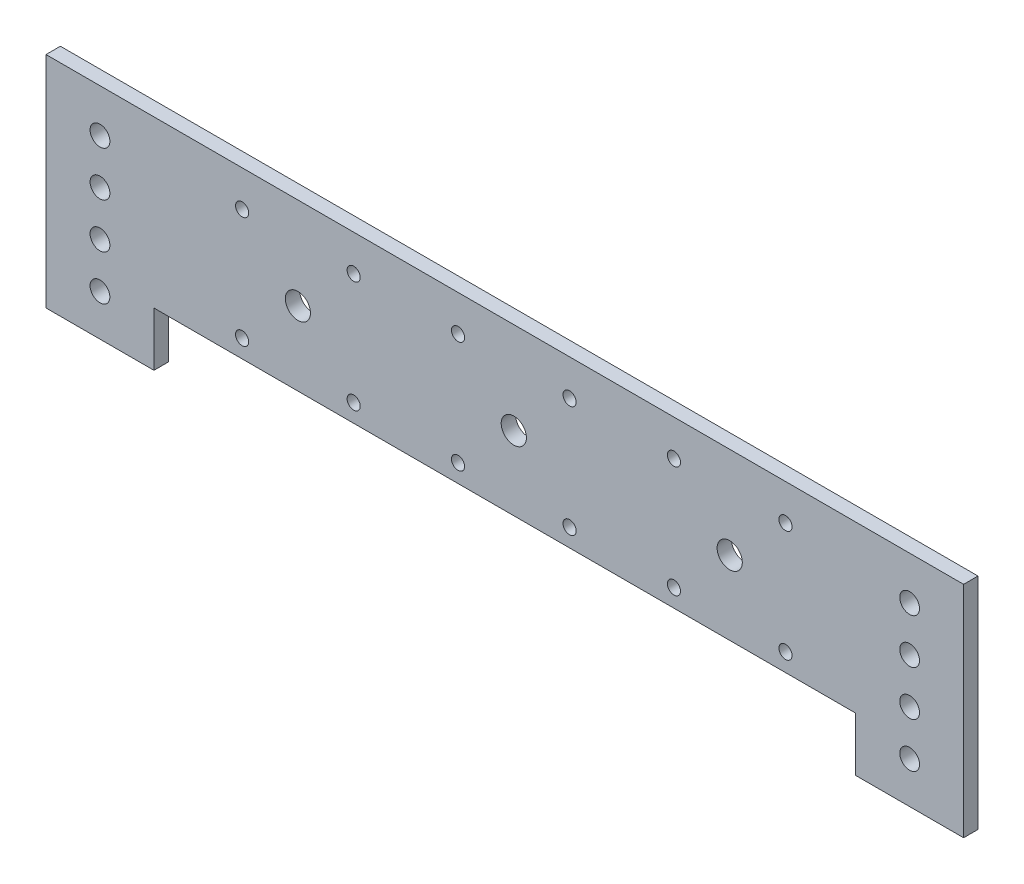
SolidWorks part; units mm, degrees
ref_plane "Front Plane" through (0, 0, 0) normal (0, 0, 1) x (1, 0, 0)
ref_plane "Top Plane" through (0, 0, 0) normal (0, 1, 0) x (1, 0, 0)
ref_plane "Right Plane" through (0, 0, 0) normal (1, 0, 0) x (0, 0, -1)
sketch "Sketch1" plane through (0, 0, 0) normal (0, 0, 1) x (1, 0, 0)
  line L0 (-30, 39.1856) -> (-30, -13) construction
  line L1 (80.5, -23) -> (-80.5, -23)
  line L2 (80.5, -23) -> (80.5, 23)
  line L3 (80.5, 23) -> (-80.5, 23)
  line L4 (-80.5, -23) -> (-80.5, 23)
  line L5 (80.5, -23) -> (-80.5, 23) construction
  line L6 (80.5, 23) -> (-80.5, -23) construction
  line L7 (-60, 39.1856) -> (-60, -72.7) construction
  line L8 (0, 39.1856) -> (0, -40.0454) construction
  line L9 (-30, 39.1856) -> (-60, 39.1856)
  line L10 (-30, 39.1856) -> (0, 39.1856)
  line L11 (-60, -72.7) -> (-53.4252, -72.7) construction
  line L12 (44.5, 13) -> (75.5, -18) construction
  line L13 (75.5, 13) -> (44.5, -18) construction
  line L19 (-75.5, 13) -> (-44.5, -18) construction
  line L20 (-15.5, 13) -> (15.5, -18) construction
  line L21 (-44.5, 13) -> (-75.5, -18) construction
  circle A0 centre (-75.5, 13) radius 1.825
  circle A1 centre (-44.5, 13) radius 1.825
  circle A2 centre (-75.5, -18) radius 1.825
  circle A3 centre (-44.5, -18) radius 1.825
  circle A4 centre (60, -2.5) radius 3.5
  circle A5 centre (-15.5, 13) radius 1.825
  circle A6 centre (15.5, 13) radius 1.825
  circle A7 centre (-15.5, -18) radius 1.825
  circle A8 centre (15.5, -18) radius 1.825
  circle A9 centre (44.5, -18) radius 1.825
  circle A10 centre (75.5, -18) radius 1.825
  circle A11 centre (-60, -2.5) radius 3.5
  circle A12 centre (0, -2.5) radius 3.5
  circle A13 centre (44.5, 13) radius 1.825
  circle A14 centre (75.5, 13) radius 1.825
  point P0 (0, 0)
  dimension "D2" = 3.65
  dimension "D5" = 5
  dimension "D8" = 3.65
  dimension "D28" = 7
  dimension "D3" = 31
  dimension "D4" = 31
  dimension "D10" = 31
  dimension "D11" = 31
  dimension "D16" = 60
  dimension "D17" = 10
  dimension "D21" = 5
  dimension "D27" = 10
extrude "Boss-Extrude1" add sketch "Sketch1" along normal blind 4
sketch "Sketch2" plane through (0, 0, 4) normal (0, 0, 1) x (1, 0, 0)
  line L1 (-80.5, -23) -> (-130, -23)
  line L2 (-80.5, -23) -> (-80.5, 23)
  line L3 (-80.5, 23) -> (-130, 23)
  line L4 (-130, -23) -> (-130, 23)
  line L5 (80.5, -23) -> (125, -23)
  line L6 (80.5, -23) -> (80.5, 23)
  line L7 (80.5, 23) -> (125, 23)
  line L8 (125, -23) -> (125, 23)
  line L9 (0, 0) -> (0, 42.9977) construction
  line L10 (-130, -23) -> (-100, -23)
  line L11 (-130, -23) -> (-130, -38)
  line L12 (-130, -38) -> (-100, -38)
  line L13 (-100, -23) -> (-100, -38)
  line L14 (125, -23) -> (95, -23)
  line L15 (125, -23) -> (125, -38)
  line L16 (125, -38) -> (95, -38)
  line L17 (95, -23) -> (95, -38)
  line M15 (-80.5, 23) -> (-80.5, -23)
  line M17 (80.5, -23) -> (80.5, 23)
  dimension "D1" = 255
  dimension "D2" = 130
  dimension "D3" = 30
  dimension "D4" = 30
  dimension "D5" = 15
extrude "Boss-Extrude2" add sketch "Sketch2" against normal up to surface (4 mm away) contours L4 L1 L3 M15 | L13 L1 L11 L12 | L5 L8 L7 M17 | L5 L17 L16 L15 up to face at (46.325, 13, 0)
hole_wizard "M5 Clearance Hole1" positions "Sketch4" profile "Sketch3" hole size "M5" standard "ISO" end condition through all
sketch "Sketch4" plane through (0, 0, 4) normal (0, 0, 1) x (1, 0, 0)
  line L3 (-95.3373, -14) -> (129.7004, -14) construction
  line L4 (95, -23) -> (-100, -23) construction
  line L5 (-130, -38) -> (-130, 23) construction
  line L6 (125, -38) -> (125, 23) construction
  line L10 (-115, 11) -> (-115, -1.5)
  line L11 (-115, -1.5) -> (-115, -14)
  line L12 (-115, -14) -> (-115, -26.5)
  line L16 (110, 11) -> (110, -1.5)
  line L17 (110, -1.5) -> (110, -14)
  line L18 (110, -14) -> (110, -26.5)
  point P0 (-115, -1.5)
  point P2 (-115, -26.5)
  point P4 (110, -1.5)
  point P6 (110, -26.5)
  point P31 (-115, 11)
  point P35 (110, 11)
  point P37 (110, -14)
  point P50 (-115, -14)
  dimension "D1" = 15
  dimension "D2" = 15
  dimension "D3" = 25
  dimension "D4" = 9
sketch "Sketch3" plane through (-115, -1.5, 4) normal (1, 0, 0) x (0, -1, 0)
  line L0 (0, 0) -> (0, 4)
  line L1 (0, 4) -> (2.75, 4)
  line L2 (2.75, 4) -> (2.75, 0)
  line L5 (2.75, 0) -> (0, 0)
  line L11 (0, -6.35) -> (0, 107.95) construction
  dimension "Thru Hole Dia." = 5.5
  dimension "Thru Hole Depth" = 4
